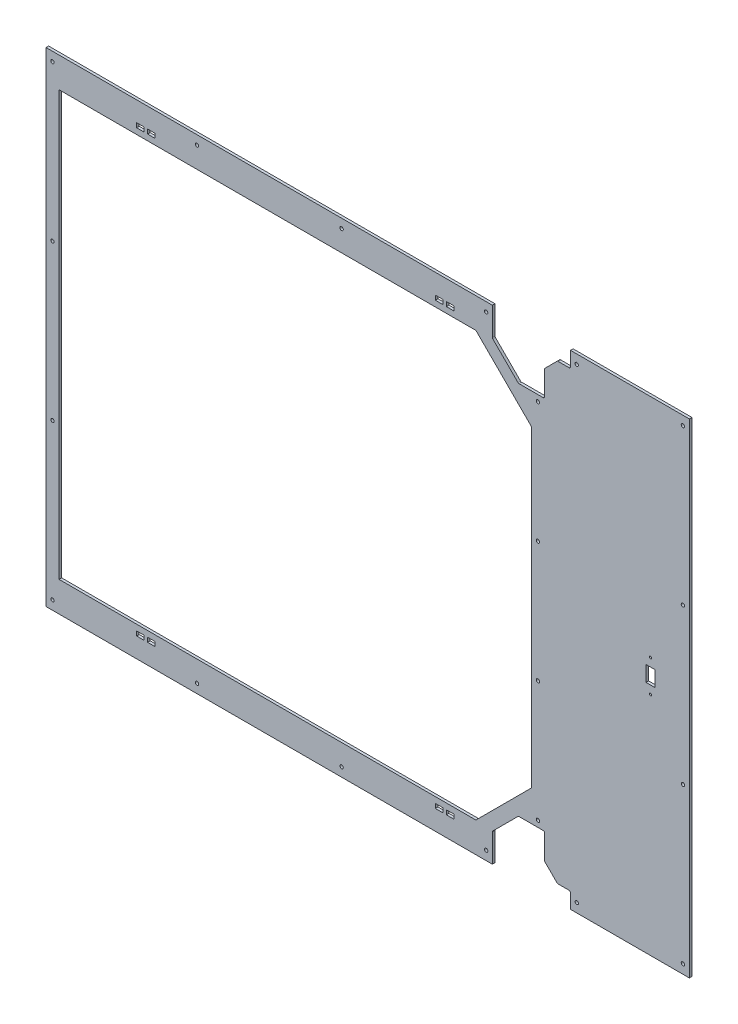
SolidWorks part; units mm, degrees
material "PC Высокая вязкость"
ref_plane "Спереди" through (0, 0, 0) normal (0, 0, 1) x (1, 0, 0)
ref_plane "Сверху" through (0, 0, 0) normal (0, 1, 0) x (1, 0, 0)
ref_plane "Справа" through (0, 0, 0) normal (1, 0, 0) x (0, 0, -1)
sketch "Эскиз1" plane through (0, 0, 0) normal (0, 0, 1) x (1, 0, 0)
  line L0 (20, 327.55) -> (20, -327.55)
  line L1 (664.1657, 327.55) -> (20, 327.55)
  line L3 (994, 374) -> (0, 374)
  line L4 (0, -374) -> (0, 374)
  line L5 (20, -327.55) -> (664.1657, -327.55)
  line L7 (994, -374) -> (0, -374)
  line L8 (690, 330) -> (770, 250) construction
  line L11 (664.1657, 327.55) -> (750, 241.7157)
  line L12 (750, 241.7157) -> (750, -241.7157)
  line L13 (750, -241.7157) -> (664.1657, -327.55)
  line L19 (994, 374) -> (994, -374)
  line L49 (770, 374) -> (770, -436.3546) construction
  point P22 (0, 0)
  point P28 (120, 46.45)
  point P37 (80.4, -0.1657)
  point P40 (80.4, -704)
  dimension "D1" = 46.45
  dimension "D2" = 690
  dimension "D3" = 46.45
  dimension "D4" = 748
  dimension "D5" = 45
  dimension "D6" = 45
  dimension "D7" = 20
  dimension "D8" = 770
  dimension "D9" = 44
  dimension "D10" = 224
  dimension "D11" = 20
  dimension "D12" = 80
  dimension "D15" = 20
extrude "Бобышка-Вытянуть1" add sketch "Эскиз1" along normal blind 4
sketch "Эскиз5" plane through (0, 0, 4) normal (0, 0, 1) x (1, 0, 0)
  line L1 (0, 374) -> (0, -374) construction
  line L2 (994, 374) -> (0, 374) construction
  line L3 (770, 330) -> (790, 350) construction
  line L4 (810, 374) -> (690, 374) construction
  line L5 (689.6, 329.8343) -> (689.6, 374.4)
  line L6 (810, 374) -> (810, 350) construction
  line L7 (810, 350) -> (790, 350) construction
  line L8 (770, 330) -> (770, 290) construction
  line L9 (770, 290) -> (730, 290) construction
  line L10 (730, 290) -> (690, 330) construction
  line L11 (690, 330) -> (690, 374) construction
  line L12 (810.4, 374.4) -> (689.6, 374.4)
  line L13 (810.4, 374.4) -> (810.4, 349.6)
  line L14 (810.4, 349.6) -> (790.1657, 349.6)
  line L15 (770.4, 329.8343) -> (790.1657, 349.6)
  line L16 (770.4, 329.8343) -> (770.4, 289.6)
  line L17 (770.4, 289.6) -> (729.8343, 289.6)
  line L18 (729.8343, 289.6) -> (689.6, 329.8343)
  line L19 (60, 0) -> (50060, 0) construction
  line L20 (750, -241.7157) -> (750, 241.7157) construction
  line L21 (770.4, -329.8343) -> (770.4, -289.6)
  line L22 (770.4, -329.8343) -> (790.1657, -349.6)
  line L23 (810.4, -349.6) -> (790.1657, -349.6)
  line L24 (810.4, -374.4) -> (810.4, -349.6)
  line L25 (810.4, -374.4) -> (689.6, -374.4)
  line L26 (689.6, -329.8343) -> (689.6, -374.4)
  line L27 (729.8343, -289.6) -> (689.6, -329.8343)
  line L28 (770.4, -289.6) -> (729.8343, -289.6)
  point P24 (750, 0)
  dimension "D1" = 45
  dimension "D2" = 44
  dimension "D3" = 690
  dimension "D4" = 40
  dimension "D5" = 40
  dimension "D6" = 40
  dimension "D7" = 40
  dimension "D8" = 24
  dimension "D9" = 20
  dimension "D10" = 45
  dimension "D11" = 20
  dimension "D12" = 20
  dimension "D13" = 0.4
extrude "Вырез-Вытянуть6" cut sketch "Эскиз5" against normal through all
sketch "Эскиз2" plane through (0, 0, 4) normal (0, 0, 1) x (1, 0, 0)
  line L0 (664.1657, 327.55) -> (20, 327.55) construction
  line L1 (0, 374) -> (0, -374) construction
  line L2 (613, 336.62) -> (613, 343.42)
  line L3 (613, 343.42) -> (601.5, 343.42)
  line L4 (601.5, 343.42) -> (601.5, 336.62)
  line L5 (601.5, 336.62) -> (613, 336.62)
  line L6 (618.5, 336.62) -> (630, 336.62)
  line L7 (630, 336.62) -> (630, 343.42)
  line L8 (629.5, 342.92) -> (619, 342.92) construction
  line L9 (629.5, 337.12) -> (629.5, 342.92) construction
  line L10 (619, 337.12) -> (629.5, 337.12) construction
  line L12 (630, 343.42) -> (618.5, 343.42)
  line L13 (618.5, 343.42) -> (618.5, 336.62)
  line L14 (80, 0) -> (-49920, 0) construction
  line L15 (729.8343, 289.6) -> (770.4, 289.6) construction
  line L19 (619, 342.92) -> (619, 337.12) construction
  line L20 (385, -84.7115) -> (385, -50084.7115) construction
  line L21 (0, 374) -> (0, -374) construction
  line L22 (770.4, -289.6) -> (729.8343, -289.6) construction
  line L23 (618.5, -343.42) -> (618.5, -336.62)
  line L24 (612.5, 337.12) -> (612.5, 342.92) construction
  line L28 (630, -343.42) -> (618.5, -343.42)
  line L29 (630, -336.62) -> (630, -343.42)
  line L30 (618.5, -336.62) -> (630, -336.62)
  line L31 (601.5, -336.62) -> (613, -336.62)
  line L32 (612.5, 342.92) -> (602, 342.92) construction
  line L34 (602, 337.12) -> (612.5, 337.12) construction
  line L35 (602, 342.92) -> (602, 337.12) construction
  line L36 (601.5, -343.42) -> (601.5, -336.62)
  line L37 (613, -343.42) -> (601.5, -343.42)
  line L38 (613, -336.62) -> (613, -343.42)
  line L39 (151.5, 343.42) -> (151.5, 336.62)
  line L40 (140, 343.42) -> (151.5, 343.42)
  line L41 (140, 336.62) -> (140, 343.42)
  line L42 (151.5, 336.62) -> (140, 336.62)
  line L43 (168.5, 336.62) -> (157, 336.62)
  line L44 (168.5, 343.42) -> (168.5, 336.62)
  line L45 (157, 343.42) -> (168.5, 343.42)
  line L46 (157, 336.62) -> (157, 343.42)
  line L47 (140, -343.42) -> (151.5, -343.42)
  line L48 (140, -336.62) -> (140, -343.42)
  line L49 (151.5, -336.62) -> (140, -336.62)
  line L50 (151.5, -343.42) -> (151.5, -336.62)
  line L51 (168.5, -343.42) -> (168.5, -336.62)
  line L52 (157, -343.42) -> (168.5, -343.42)
  line L53 (157, -336.62) -> (157, -343.42)
  line L54 (168.5, -336.62) -> (157, -336.62)
  line L55 (770, 289.6) -> (770, -289.6) construction
  point P7 (0, 0)
  dimension "D1" = 5.8
  dimension "D2" = 10.5
  dimension "D3" = 6.5
  dimension "D4" = 10.5
  dimension "D5" = 9.57
  dimension "D6" = 385
  dimension "D8" = 385
  dimension "D10" = 140
  dimension "D11" = 770
  dimension "D12" = 140
  dimension "D7" = 0.5
extrude "Вырез-Вытянуть1" cut sketch "Эскиз2" against normal through all
sketch "Эскиз3" plane through (0, 0, 4) normal (0, 0, 1) x (1, 0, 0)
  line L2 (689.6, 374) -> (0, 374) construction
  line L3 (140, 343.42) -> (140, 336.62) construction
  line L5 (0, 374) -> (0, -374) construction
  line L6 (10, 360) -> (10, 120) construction
  line L7 (0, -374) -> (689.6, -374) construction
  line L8 (10, 360) -> (233.33, 360) construction
  line L9 (151.5, 343.42) -> (140, 343.42) construction
  line L10 (689.6, 374) -> (689.6, 329.8343) construction
  line L13 (10, -360) -> (233.33, -360) construction
  line L14 (994, 374) -> (810.4, 374) construction
  line L15 (994, -374) -> (994, 374) construction
  line L16 (984, 360) -> (984, 120) construction
  line L17 (810.4, -374) -> (994, -374) construction
  line L18 (984, -360) -> (820, -360) construction
  line L19 (810.4, 349.6) -> (810.4, 374) construction
  line L20 (729.8343, 289.6) -> (770.4, 289.6) construction
  line L21 (770, 289.6) -> (770, -289.6) construction
  line L22 (770.4, -289.6) -> (729.8343, -289.6) construction
  line L24 (760, 280) -> (760, 93.33) construction
  circle A41 centre (10, 360) radius 2.6
  circle A42 centre (10, 120) radius 2.6
  circle A43 centre (10, -120) radius 2.6
  circle A44 centre (10, -360) radius 2.6
  circle A45 centre (233.33, 360) radius 2.6
  circle A46 centre (456.66, 360) radius 2.6
  circle A47 centre (679.99, 360) radius 2.6
  circle A48 centre (233.33, -360) radius 2.6
  circle A49 centre (456.66, -360) radius 2.6
  circle A50 centre (679.99, -360) radius 2.6
  circle A51 centre (984, 360) radius 2.6
  circle A52 centre (984, 120) radius 2.6
  circle A53 centre (984, -120) radius 2.6
  circle A54 centre (984, -360) radius 2.6
  circle A55 centre (820, -360) radius 2.6
  circle A56 centre (820, 360) radius 2.6
  circle A57 centre (760, 280) radius 2.6
  circle A58 centre (760, 93.33) radius 2.6
  circle A59 centre (760, -93.34) radius 2.6
  circle A60 centre (760, -280.01) radius 2.6
  dimension "D1" = 5.2
  dimension "D2" = 10
  dimension "D10" = 4
  dimension "D8" = 223.33
  dimension "D9" = 9.61
  dimension "D12" = 5.2
  dimension "D13" = 14
  dimension "D14" = 10
  dimension "D18" = 2
  dimension "D22" = 5.2
  dimension "D23" = 10
  dimension "D3" = 14
  dimension "D5" = 240
  dimension "D6" = 14
  dimension "D7" = 4
  dimension "D11" = 223.33
  dimension "D16" = 240
  dimension "D17" = 14
  dimension "D19" = 164
  dimension "D20" = 9.6
  dimension "D21" = 770
  dimension "D24" = 94
  dimension "D25" = 4
  dimension "D26" = 186.67
  dimension "D27" = 9.59
  dimension "D4" = 4
  dimension "D15" = 4
extrude "Вырез-Вытянуть4" cut sketch "Эскиз3" against normal through all
sketch "Эскиз6" plane through (0, 0, 4) normal (0, 0, 1) x (1, 0, 0)
  line L0 (994, 0) -> (-49006, 0) construction
  line L5 (994, -374) -> (994, 374) construction
  line L7 (934, 24.8) -> (934, -24.8) construction
  line L11 (941, -12) -> (941, 12)
  line L12 (927, -12) -> (941, -12)
  line L13 (941, 12) -> (927, 12)
  line L14 (927, 12) -> (927, -12)
  circle A6 centre (934, 24.8) radius 1.75
  circle A7 centre (934, -24.8) radius 1.75
  point P8 (994, 0)
  point P22 (934, 12)
  point P24 (934, 0)
  point P30 (941, 0)
  dimension "D9" = 3.5
  dimension "D10" = 49.6
  dimension "D2" = 60
  dimension "D7" = 24
  dimension "D8" = 14
extrude "Вырез-Вытянуть7" cut sketch "Эскиз6" against normal through all
fillet "Скругление1" radius 2.5 12 edges at (790.1657, -349.6, 2) (810.4, -349.6, 2) (770.4, -329.8343, 2) (770.4, -289.6, 2) (729.8343, -289.6, 2) (689.6, -329.8343, 2) (689.6, 329.8343, 2) (810.4, 349.6, 2) (790.1657, 349.6, 2) (770.4, 329.8343, 2) (770.4, 289.6, 2) (729.8343, 289.6, 2)
